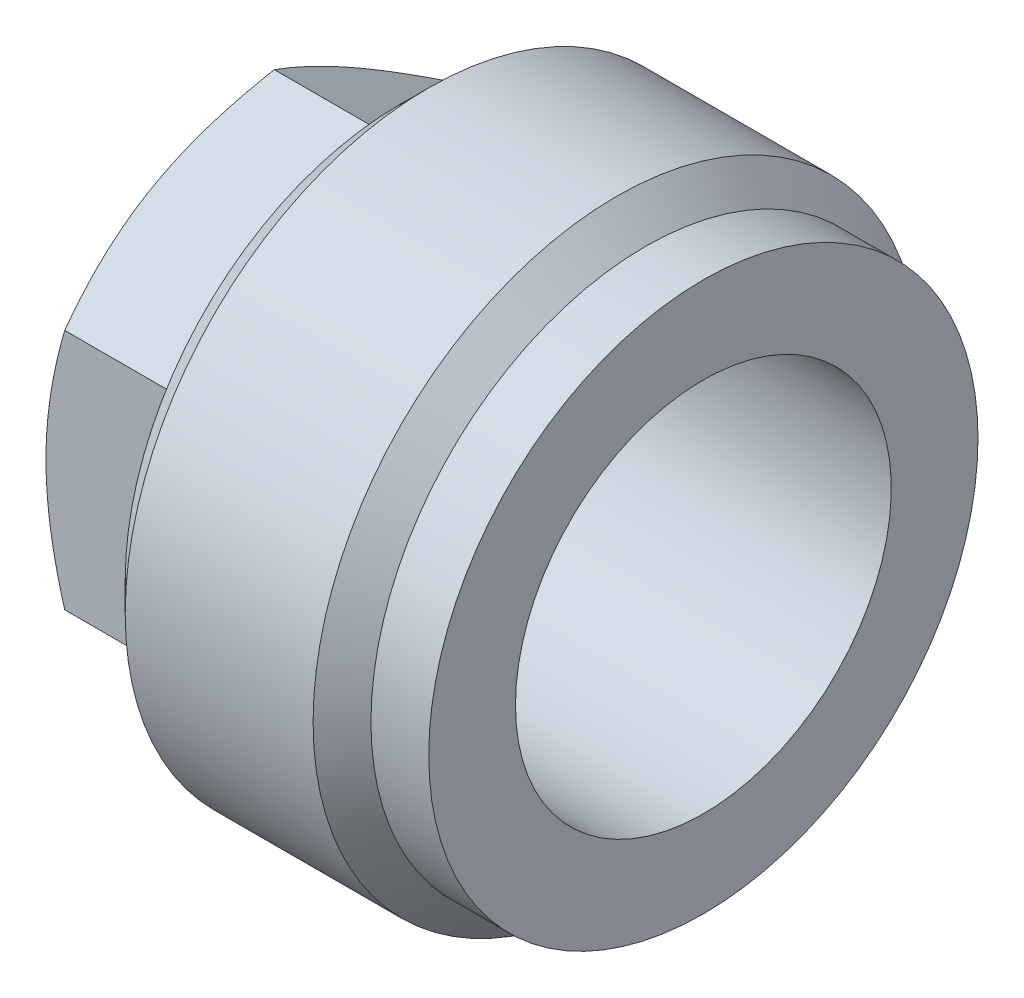
SolidWorks part; units mm, degrees
ref_plane "Спереди" through (0, 0, 0) normal (0, 0, 1) x (1, 0, 0)
ref_plane "Сверху" through (0, 0, 0) normal (0, 1, 0) x (1, 0, 0)
ref_plane "Справа" through (0, 0, 0) normal (1, 0, 0) x (0, 0, -1)
sketch "Эскиз1" plane through (0, 0, 0) normal (0, 0, 1) x (1, 0, 0)
  line L0 (0, 0) -> (60.2411, 0) construction
  line L1 (0, -9.188) -> (0, -11)
  line L2 (0, -11) -> (3.7528, -17.5)
  line L3 (3.7528, -17.5) -> (12, -17.5)
  line L4 (12, -17.5) -> (12, -21)
  line L5 (12, -21) -> (27, -21)
  line L6 (27, -21) -> (29, -19)
  line L7 (29, -19) -> (33, -19)
  line L8 (33, -19) -> (33, -13)
  line L9 (33, -13) -> (13, -13)
  line L10 (13, -13) -> (13, -9.188)
  line L11 (13, -9.188) -> (0, -9.188)
  dimension "D1" = 35
  dimension "D2" = 30
  dimension "D3" = 22
  dimension "D4" = 18.376
  dimension "D5" = 33
  dimension "D6" = 26
  dimension "D7" = 38
  dimension "D8" = 42
  dimension "D9" = 45
  dimension "D10" = 4
  dimension "D11" = 20
  dimension "D12" = 12
revolve "Повернуть1" add sketch "Эскиз1" angle 360 about L0
cosmetic thread "Условное изображение резьбы1" parameters "D2"=40.376
cosmetic thread "Условное изображение резьбы2" parameters "D2"=20
sketch "Эскиз2" plane through (0, 0, 0) normal (-1, 0, 0) x (0, 0, 1)
  line L1 (0, 16.7432) -> (-14.5, 8.3716)
  line L2 (-14.5, 8.3716) -> (-14.5, -8.3716)
  line L3 (-14.5, -8.3716) -> (0, -16.7432)
  line L4 (0, -16.7432) -> (14.5, -8.3716)
  line L5 (14.5, -8.3716) -> (14.5, 8.3716)
  line L6 (14.5, 8.3716) -> (0, 16.7432)
  circle A0 centre (0, 0) radius 17.5 construction
  circle A1 centre (0, 0) radius 17.5
  circle A2 centre (0, 0) radius 14.5 construction
  point P3 (0, 0)
  point P11 (0, 15.8995)
  dimension "D1" = 29
extrude "Вырез-Вытянуть1" cut sketch "Эскиз2" against normal up to surface (12 mm away) contours L2 A1 | L6 A1 | L1 A1 | L5 A1 | L4 A1 | L3 A1
chamfer "Фаска1" distance 2 angle 45 1 edges at (12, 0, 21)
chamfer "Фаска2" distance 1.6 angle 45 1 edges at (0, 0, 9.188)
